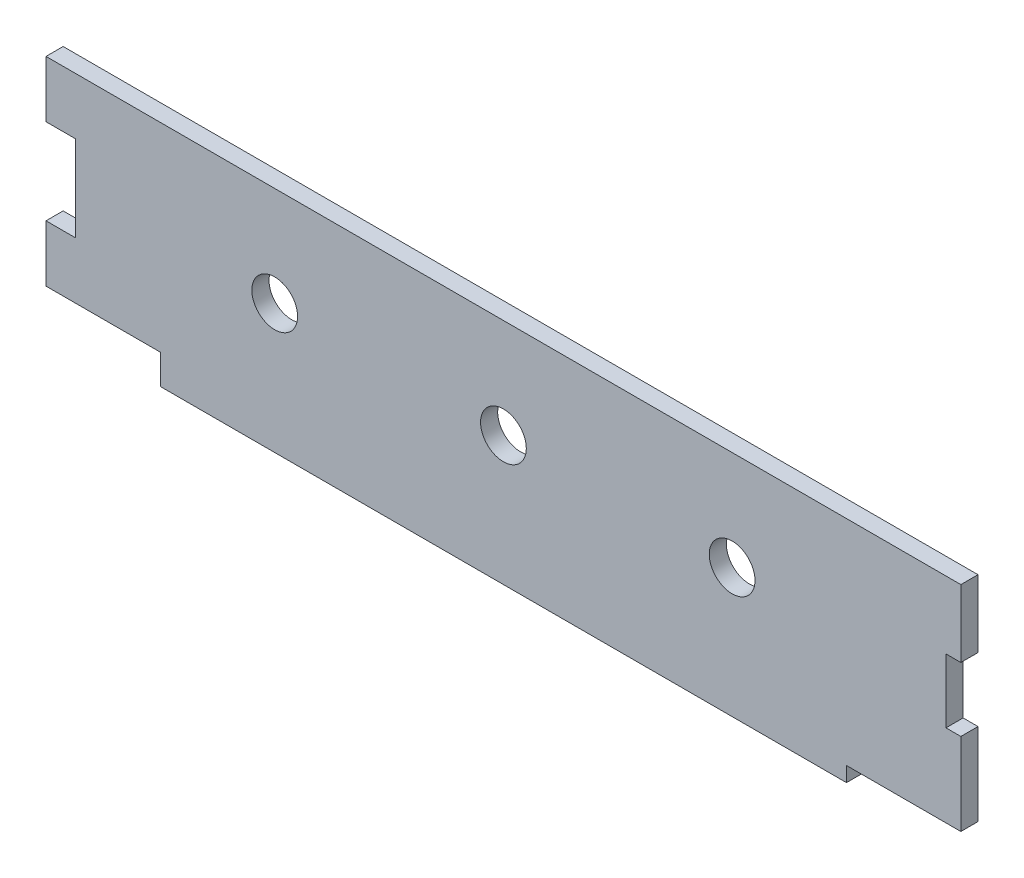
SolidWorks part; units mm, degrees
ref_plane "Alzado" through (0, 0, 0) normal (0, 0, 1) x (1, 0, 0)
ref_plane "Planta" through (0, 0, 0) normal (0, 1, 0) x (1, 0, 0)
ref_plane "Vista lateral" through (0, 0, 0) normal (1, 0, 0) x (0, 0, -1)
sketch "Croquis1" plane through (0, 0, 0) normal (0, 0, 1) x (1, 0, 0)
  line L0 (-40, 8.7) -> (40, 8.7)
  line L1 (40, 8.7) -> (40, 2.8)
  line L2 (40, 2.8) -> (38.7, 2.8)
  line L3 (38.7, 2.8) -> (38.7, -2.8)
  line L4 (38.7, -2.8) -> (40, -2.8)
  line L5 (40, -2.8) -> (40, -10)
  line L6 (40, -10) -> (30, -10)
  line L7 (30, -10) -> (30, -11.3)
  line L8 (30, -11.3) -> (-30, -11.3)
  line L9 (-30, -11.3) -> (-30, -8.7)
  line L10 (-30, -8.7) -> (-40, -8.7)
  line L11 (-40, -8.7) -> (-40, -3.75)
  line L12 (-40, -3.75) -> (-37.4, -3.75)
  line L13 (-37.4, -3.75) -> (-37.4, 3.75)
  line L14 (-37.4, 3.75) -> (-40, 3.75)
  line L15 (-40, 3.75) -> (-40, 8.7)
  line L16 (38.7, 0) -> (-37.4, 0) construction
  circle A0 centre (20, 0) radius 2
  circle A1 centre (0, 0) radius 2
  circle A2 centre (-20, 0) radius 2
  point P16 (-37.4, 0)
  point P18 (38.7, 0)
  point P19 (0, 8.7)
  dimension "D9" = 4
  dimension "D10" = 20
  dimension "D11" = 20
  dimension "D12" = 20
  dimension "D1" = 80
  dimension "D2" = 10
  dimension "D3" = 10
  dimension "D4" = 20
  dimension "D5" = 7.5
  dimension "D6" = 5.6
  dimension "D7" = 2.6
  dimension "D8" = 1.3
extrude "Saliente-Extruir1" add sketch "Croquis1" along normal blind 1.5
